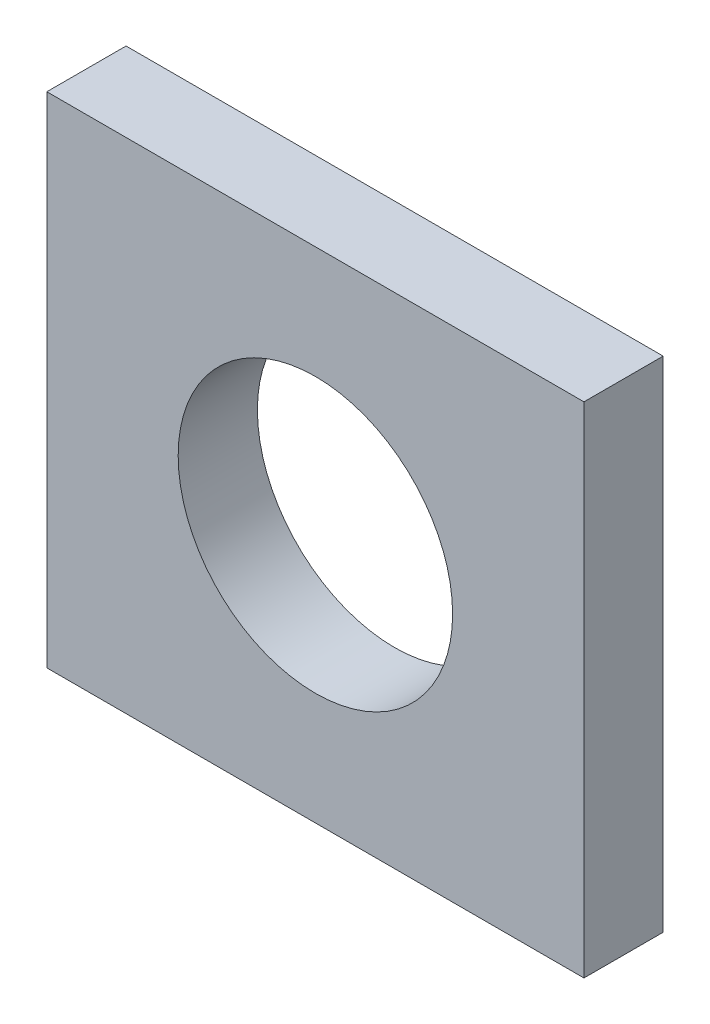
SolidWorks part; units mm, degrees
ref_plane "Front Plane" through (0, 0, 0) normal (0, 0, 1) x (1, 0, 0)
ref_plane "Top Plane" through (0, 0, 0) normal (0, 1, 0) x (1, 0, 0)
ref_plane "Right Plane" through (0, 0, 0) normal (1, 0, 0) x (0, 0, -1)
sketch "Sketch1" plane through (0, 0, 0) normal (0, 0, 1) x (1, 0, 0)
  line L1 (-43.0563, 40) -> (0, 40)
  line L2 (-43.0563, 40) -> (-43.0563, 0)
  line L3 (-43.0563, 0) -> (0, 0)
  line L4 (0, 40) -> (0, 0)
extrude "Boss-Extrude1" add sketch "Sketch1" along normal blind 6.35
sketch "Sketch2" plane through (0, 0, 6.35) normal (0, 0, 1) x (1, 0, 0)
  line L0 (-21.5282, 0) -> (-21.5282, 40) construction
  line L1 (-43.0563, 0) -> (0, 0) construction
  line L2 (0, 40) -> (-43.0563, 40) construction
  circle A0 centre (-21.5282, 20) radius 11
extrude "Cut-Extrude1" cut sketch "Sketch2" against normal blind 10
